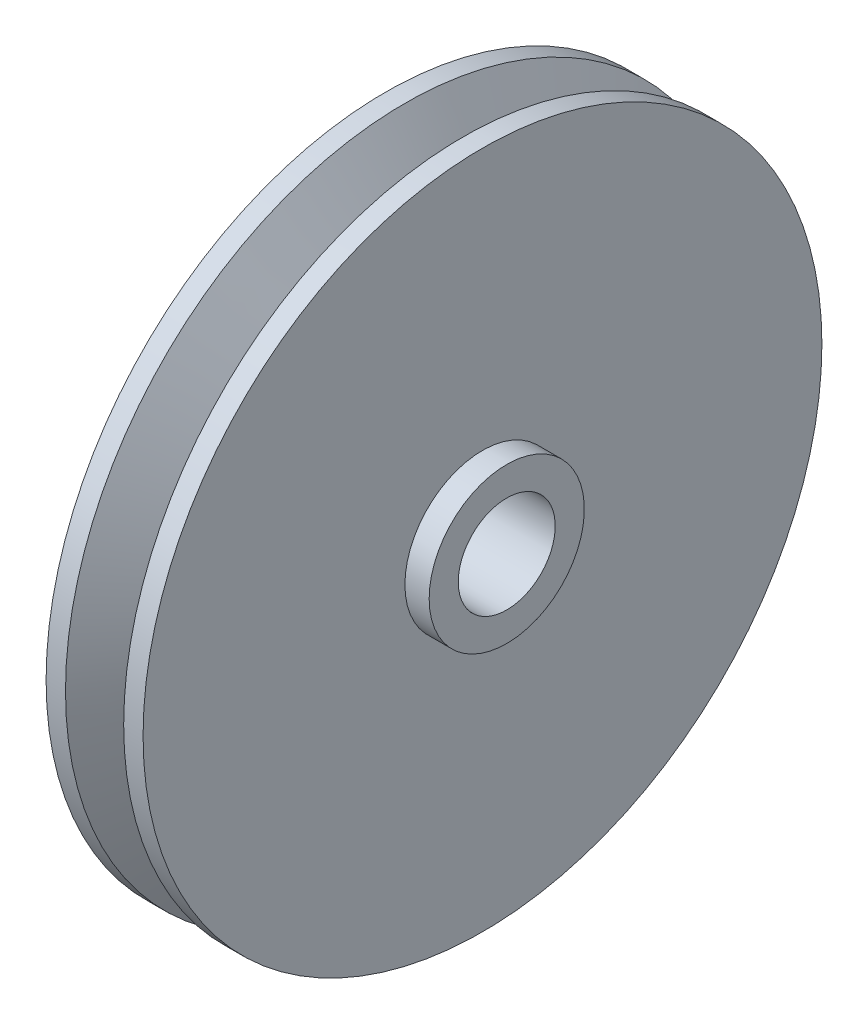
SolidWorks part; units mm, degrees
ref_plane "Front" through (0, 0, 0) normal (0, 0, 1) x (1, 0, 0)
ref_plane "Top" through (0, 0, 0) normal (0, 1, 0) x (1, 0, 0)
ref_plane "Right" through (0, 0, 0) normal (1, 0, 0) x (0, 0, -1)
sketch "Sketch1" plane through (0, 0, 0) normal (0, 0, 1) x (1, 0, 0)
  line L0 (0, 0) -> (34.9193, 0) construction
  line L1 (0, 6.35) -> (0, 44.45)
  line L2 (0, 44.45) -> (2.54, 44.45)
  line L3 (6.35, 38.1) -> (6.35, 55.379) construction
  line L4 (2.54, 44.45) -> (6.35, 38.1)
  line L5 (10.16, 44.45) -> (12.7, 44.45)
  line L6 (12.7, 44.45) -> (12.7, 10.16)
  line L7 (12.7, 10.16) -> (15.875, 10.16)
  line L8 (15.875, 10.16) -> (15.875, 6.35)
  line L9 (15.875, 6.35) -> (0, 6.35)
  line L10 (6.35, 38.1) -> (10.16, 44.45)
revolve "Revolve1" add sketch "Sketch1" angle 360 about L0
